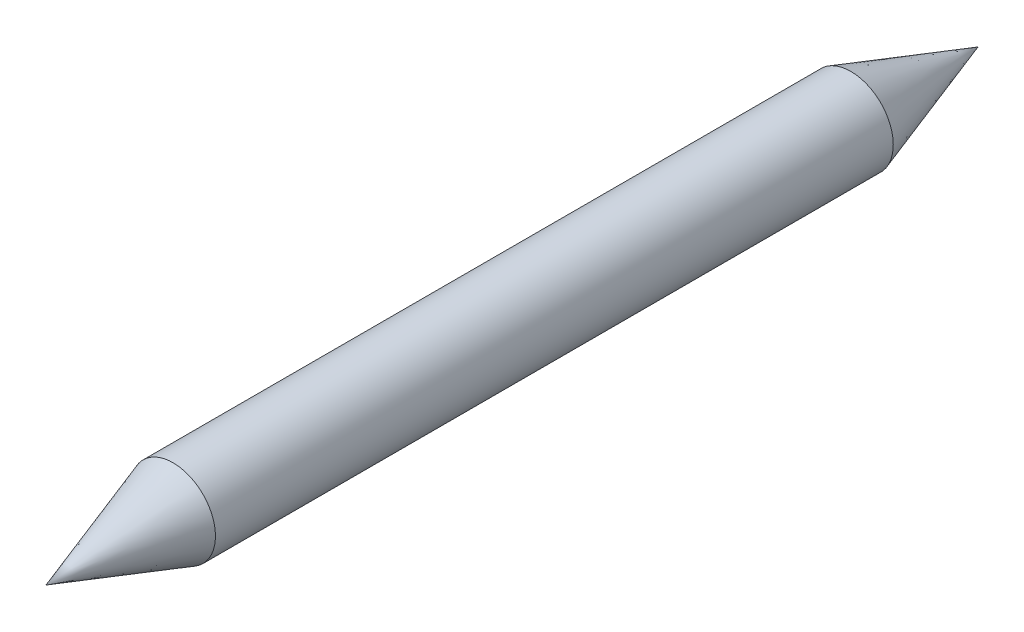
SolidWorks part; units mm, degrees
ref_plane "Front Plane" through (0, 0, 0) normal (0, 0, 1) x (1, 0, 0)
ref_plane "Top Plane" through (0, 0, 0) normal (0, 1, 0) x (1, 0, 0)
ref_plane "Right Plane" through (0, 0, 0) normal (1, 0, 0) x (0, 0, -1)
sketch "Sketch1" plane through (0, 0, 0) normal (0, 0, 1) x (1, 0, 0)
  circle A0 centre (0, 0) radius 10
  circle A1 centre (0, 0) radius 9
  dimension "D1" = 20
  dimension "D2" = 18
extrude "Boss-Extrude1" add sketch "Sketch1" against normal blind 160
ref_plane "Plane1" through (0, 0, 30) normal (0, 0, 1) x (1, 0, 0)
sketch "Sketch2" plane through (0, 0, 30) normal (0, 0, 1) x (1, 0, 0)
  point P0 (0, 0)
sketch "Sketch3" plane through (0, 0, 0) normal (0, 0, 1) x (1, 0, 0)
  circle A1 centre (0, 0) radius 10
  circle A2 centre (0, 0) radius 10
  dimension "D1" = 0
ref_plane "Plane2" through (0, 0, -190) normal (0, 0, -1) x (-1, 0, 0)
sketch "Sketch4" plane through (0, 0, -190) normal (0, 0, -1) x (-1, 0, 0)
  point P0 (0, 0)
sketch "Sketch5" plane through (0, 0, -160) normal (0, 0, -1) x (-1, 0, 0)
  circle A1 centre (0, 0) radius 10
  circle A2 centre (0, 0) radius 10
  dimension "D1" = 0
sketch "Sketch6" plane through (0, 0, 0) normal (0, 0, 1) x (1, 0, 0)
  circle A0 centre (0, 0) radius 10 construction
  circle A1 centre (0, 0) radius 10
loft "Loft3" add profiles "Sketch3", "Sketch2"
sketch "Sketch7" plane through (0, 0, -160) normal (0, 0, -1) x (-1, 0, 0)
  circle A0 centre (0, 0) radius 10 construction
  circle A1 centre (0, 0) radius 10
loft "Loft4" add profiles "Sketch7", "Sketch4"
